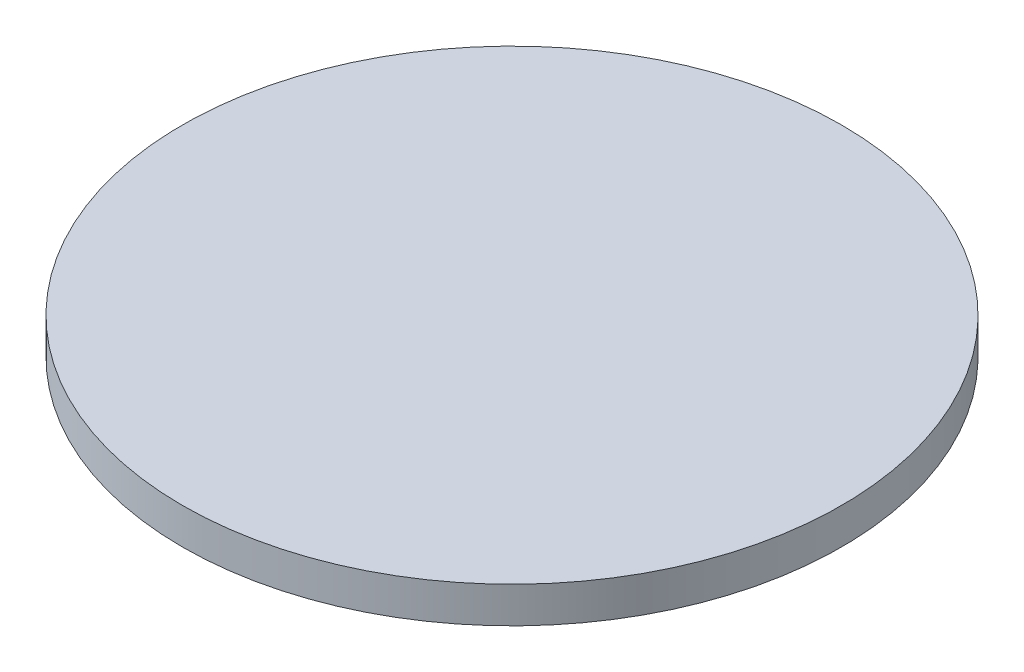
SolidWorks part; units mm, degrees
ref_plane "Front" through (0, 0, 0) normal (0, 0, 1) x (1, 0, 0)
ref_plane "Top" through (0, 0, 0) normal (0, 1, 0) x (1, 0, 0)
ref_plane "Right" through (0, 0, 0) normal (1, 0, 0) x (0, 0, -1)
sketch "Sketch1" plane through (0, 0, 0) normal (0, 1, 0) x (1, 0, 0)
  circle A2 centre (0, 0) radius 64
  dimension "D1" = 128
extrude "Boss-Extrude1" add sketch "Sketch1" along normal blind 7 contours A2
